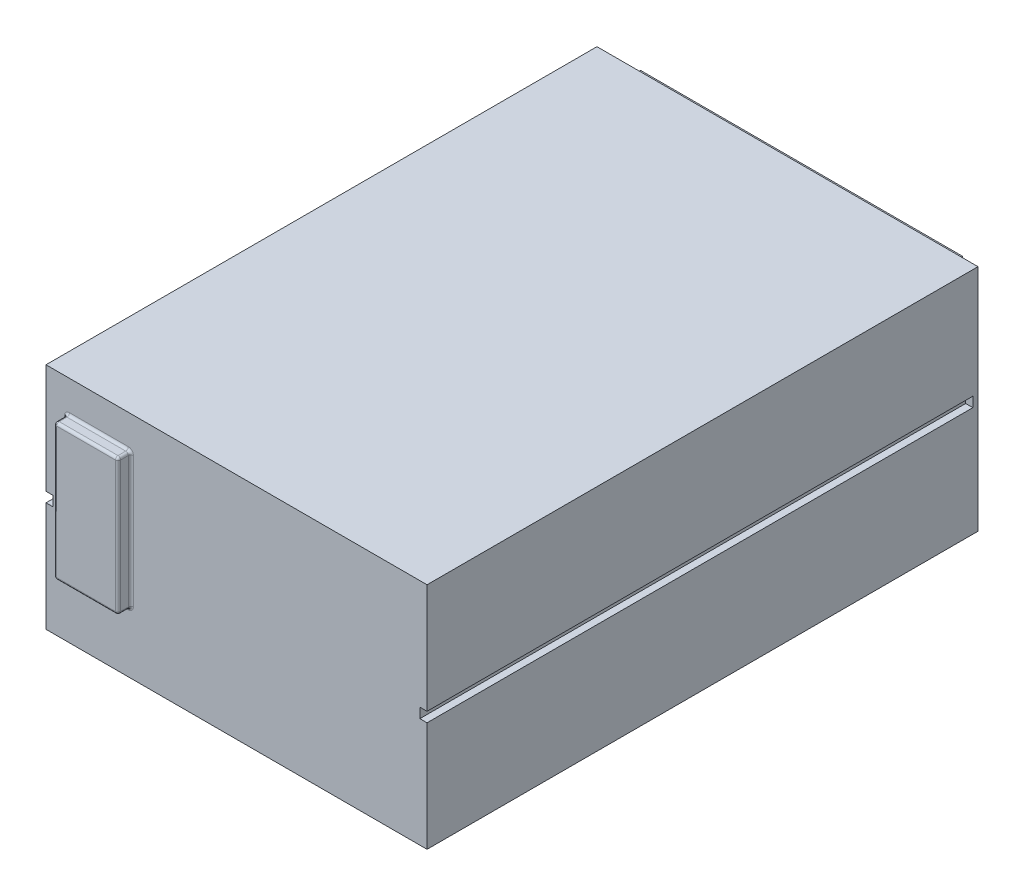
SolidWorks part; units mm, degrees
ref_plane "Front" through (0, 0, 0) normal (0, 0, 1) x (1, 0, 0)
ref_plane "Top" through (0, 0, 0) normal (0, 1, 0) x (1, 0, 0)
ref_plane "Right" through (0, 0, 0) normal (1, 0, 0) x (0, 0, -1)
sketch "Sketch1" plane through (0, 0, 0) normal (0, 1, 0) x (1, 0, 0)
  line L1 (-74, 107) -> (74, 107)
  line L2 (-74, 107) -> (-74, -107)
  line L3 (-74, -107) -> (74, -107)
  line L4 (74, 107) -> (74, -107)
  line L5 (-74, 107) -> (74, -107) construction
  line L6 (-74, -107) -> (74, 107) construction
  point P0 (0, 0)
  dimension "D1" = 214
  dimension "D2" = 148
extrude "Boss-Extrude1" add sketch "Sketch1" along normal blind 89
sketch "Sketch2" plane through (0, 0, 107) normal (0, 0, 1) x (1, 0, 0)
  line L0 (-74, 89) -> (-74, 0) construction
  line L1 (-76.7831, 46.4319) -> (-71.2169, 46.4319)
  line L2 (-76.7831, 46.4319) -> (-76.7831, 42.5681)
  line L3 (-76.7831, 42.5681) -> (-71.2169, 42.5681)
  line L4 (-71.2169, 46.4319) -> (-71.2169, 42.5681)
  line L5 (-76.7831, 46.4319) -> (-71.2169, 42.5681) construction
  line L6 (-76.7831, 42.5681) -> (-71.2169, 46.4319) construction
  point P0 (-74, 44.5)
  point P7 (-71.2169, 42.5681)
extrude "Cut-Extrude1" cut sketch "Sketch2" against normal blind 212
mirror "Mirror1" about plane through (0, 0, 0) normal (1, 0, 0) of "Cut-Extrude1"
sketch "Sketch3" plane through (0, 0, 107) normal (0, 0, 1) x (1, 0, 0)
  line L1 (-65.8634, 76.4366) -> (-41.0375, 76.4366)
  line L2 (-65.8634, 76.4366) -> (-65.8634, 23.5182)
  line L3 (-65.8634, 23.5182) -> (-41.0375, 23.5182)
  line L4 (-41.0375, 76.4366) -> (-41.0375, 23.5182)
  line L5 (-65.8634, 76.4366) -> (-41.0375, 23.5182) construction
  line L6 (-65.8634, 23.5182) -> (-41.0375, 76.4366) construction
  point P0 (-53.4504, 49.9774)
extrude "Boss-Extrude2" add sketch "Sketch3" along normal blind 5
fillet "Fillet1" radius 1 12 edges at (-53.4504, 23.5182, 112) (-65.8634, 49.9774, 112) (-53.4504, 76.4366, 112) (-41.0375, 49.9774, 112) (-53.4504, 23.5182, 107) (-41.0375, 49.9774, 107) (-53.4504, 76.4366, 107) (-65.8634, 49.9774, 107) (-41.0375, 23.5182, 109.5) (-41.0375, 76.4366, 109.5) (-65.8634, 23.5182, 109.5) (-65.8634, 76.4366, 109.5)
sketch "Sketch4" plane through (0, 0, -107) normal (0, 0, -1) x (-1, 0, 0)
  line L0 (-74, 89) -> (74, 89) construction
  line L1 (-66.9205, 88.5) -> (58.0795, 88.5)
  line L2 (-66.9205, 88.5) -> (-66.9205, 59.5)
  line L3 (-66.9205, 59.5) -> (58.0795, 59.5)
  line L4 (58.0795, 88.5) -> (58.0795, 59.5)
  line L5 (-66.9205, 88.5) -> (58.0795, 59.5) construction
  line L6 (-66.9205, 59.5) -> (58.0795, 88.5) construction
  point P0 (-4.4205, 74)
  dimension "D1" = 29
  dimension "D2" = 125
  dimension "D3" = 0.5
extrude "Boss-Extrude3" add sketch "Sketch4" along normal blind 1
pattern_linear "LPattern1" count 3 spacing 29.5 along (0, -1, 0) of "Boss-Extrude3"
